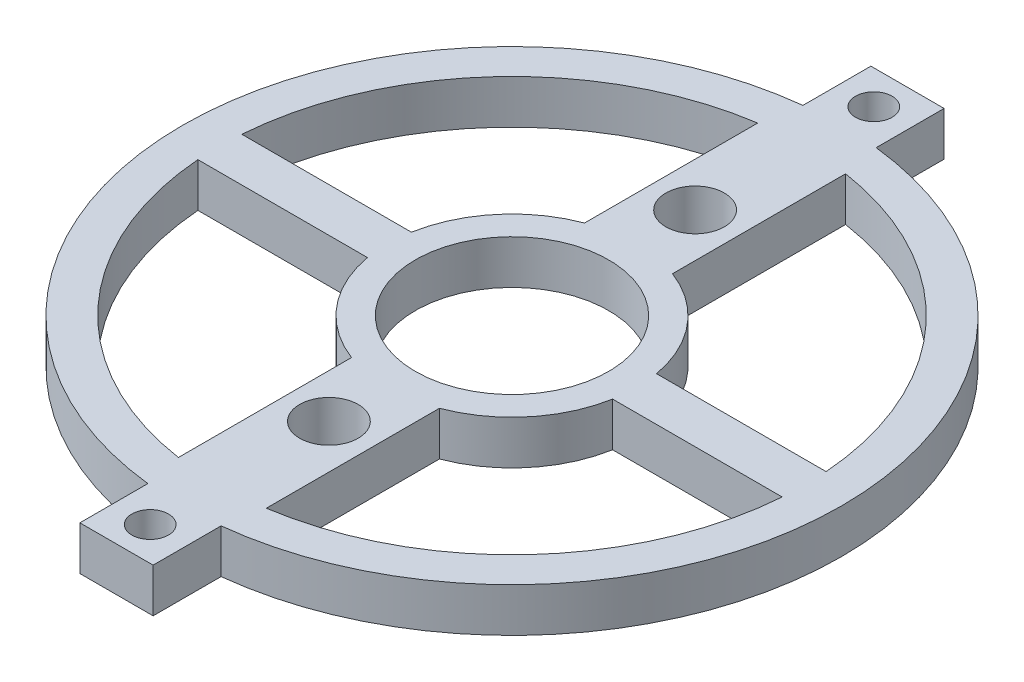
SolidWorks part; units mm, degrees
material "Custom Plastic"
ref_plane "Front Plane" through (0, 0, 0) normal (0, 0, 1) x (1, 0, 0)
ref_plane "Top Plane" through (0, 0, 0) normal (0, 1, 0) x (1, 0, 0)
ref_plane "Right Plane" through (0, 0, 0) normal (1, 0, 0) x (0, 0, -1)
sketch "Sketch1" plane through (0, 0, 0) normal (0, 1, 0) x (1, 0, 0)
  circle A0 centre (0, 0) radius 22.5
  circle A1 centre (0, 0) radius 20
  dimension "D1" = 40
  dimension "D2" = 45
extrude "Boss-Extrude1" add sketch "Sketch1" along normal blind 3
sketch "Sketch2" plane through (0, 0, 0) normal (0, 1, 0) x (1, 0, 0)
  line L0 (0, 27) -> (0, 24.7) construction
  line L1 (-2.5, 27) -> (2.5, 27)
  line L2 (-2.5, 27) -> (-2.5, 22.3607)
  line L4 (2.5, 27) -> (2.5, 22.3607)
  circle A0 centre (0, 0) radius 22.5 construction
  arc A1 (2.5, 22.3607) -> (-2.5, 22.3607) centre (0, 0) ccw
  circle A2 centre (0, 24.7) radius 1.25
  dimension "D5" = 2.5
  dimension "D1" = 27
  dimension "D2" = 5
  dimension "D3" = 0
  dimension "D4" = 24.7
extrude "Boss-Extrude2" add sketch "Sketch2" along normal blind 3
pattern_circular "CirPattern1" count 2 over 360 about axis through (0, 0, 0) along (0, 1, 0) of "Boss-Extrude2"
sketch "Sketch3" plane through (0, 0, 0) normal (0, 1, 0) x (1, 0, 0)
  line L0 (-3, 19.7737) -> (-3, 7.953)
  line L1 (3, 19.7737) -> (3, 7.953)
  line L2 (-19.9437, 1.5) -> (-8.3666, 1.5)
  line L3 (-19.9437, -1.5) -> (-8.3666, -1.5)
  line L4 (19.9437, 1.5) -> (8.3666, 1.5)
  line L5 (19.9437, -1.5) -> (8.3666, -1.5)
  line L6 (3, -7.953) -> (3, -19.7737)
  line L7 (-3, -7.953) -> (-3, -19.7737)
  circle A0 centre (0, 0) radius 20 construction
  arc A1 (-8.3666, -1.5) -> (-3, -7.953) centre (0, 0) ccw
  circle A2 centre (0, 0) radius 6.6
  arc A3 (-19.9437, 1.5) -> (-19.9437, -1.5) centre (0, 0) ccw
  arc A4 (3, 19.7737) -> (-3, 19.7737) centre (0, 0) ccw
  arc A5 (19.9437, -1.5) -> (19.9437, 1.5) centre (0, 0) ccw
  arc A6 (-3, -19.7737) -> (3, -19.7737) centre (0, 0) ccw
  arc A7 (-3, 7.953) -> (-8.3666, 1.5) centre (0, 0) ccw
  arc A8 (8.3666, 1.5) -> (3, 7.953) centre (0, 0) ccw
  arc A9 (3, -7.953) -> (8.3666, -1.5) centre (0, 0) ccw
  dimension "D1" = 13.2
  dimension "D2" = 17
  dimension "D3" = 1.5
  dimension "D4" = 1.5
  dimension "D5" = 1.5
  dimension "D6" = 1.5
  dimension "D7" = 3
  dimension "D8" = 3
extrude "Boss-Extrude3" add sketch "Sketch3" along normal blind 3
sketch "Sketch4" plane through (0, 3, 0) normal (0, 1, 0) x (1, 0, 0)
  circle A0 centre (0, 12.5) radius 2
  circle A1 centre (0, -12.5) radius 2
  dimension "D3" = 4
  dimension "D4" = 4
  dimension "D1" = 12.5
  dimension "D2" = 12.5
extrude "Cut-Extrude1" cut sketch "Sketch4" against normal up to vertex (3 mm away) up to point (0, 0, 0)
